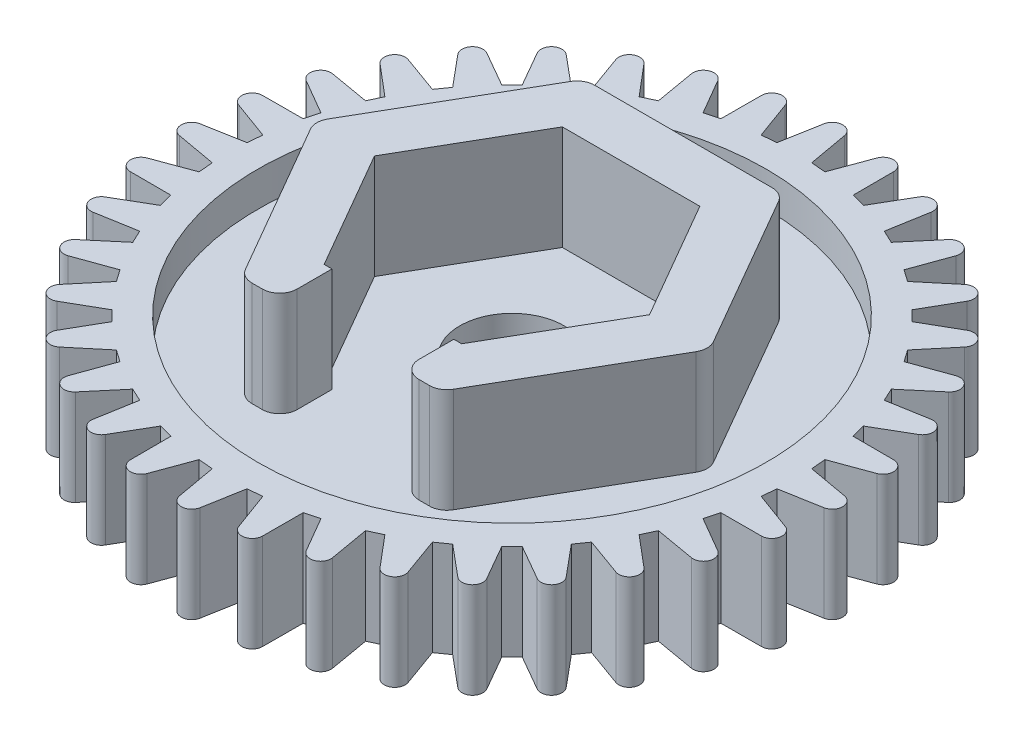
SolidWorks part; units mm, degrees
material "ABS"
ref_plane "Front Plane" through (0, 0, 0) normal (0, 0, 1) x (1, 0, 0)
ref_plane "Top Plane" through (0, 0, 0) normal (0, 1, 0) x (1, 0, 0)
ref_plane "Right Plane" through (0, 0, 0) normal (1, 0, 0) x (0, 0, -1)
sketch "Sketch1" plane through (0, 0, 0) normal (0, 0, 1) x (1, 0, 0)
  line L0 (1.5, 0) -> (7.3, 0)
  line L1 (7.3, 0) -> (7.3, 1)
  line L2 (7.3, 1) -> (9.5, 1)
  line L3 (9.5, 1) -> (9.5, -1.75)
  line L8 (0, 3) -> (0, 0) construction
  line L9 (7.3, -2) -> (1.5, -2)
  line L11 (7.3, -2) -> (7.3, -1.75)
  line L12 (7.3, -1.75) -> (9.5, -1.75)
  line L14 (1.5, -2) -> (1.5, 0)
  dimension "D1" = 19
  dimension "D2" = 2.2
  dimension "D4" = 0.25
  dimension "D5" = 2.75
  dimension "D8" = 3
revolve "Revolve1" add sketch "Sketch1" angle 360 about L8
sketch "Sketch2" plane through (0, 1, 0) normal (0, 1, 0) x (1, 0, 0)
  line L0 (0, 0) -> (0, 8.125) construction
  line L1 (0, 8.125) -> (0, 9.2) construction
  line L2 (-0.2953, 9.2529) -> (-0.5, 8.1096)
  line L3 (0, 9.2) -> (0, 9.5) construction
  line L4 (0.2953, 9.2529) -> (0.5, 8.1096)
  line L5 (1.8976, 9.061) -> (1.9006, 7.8996)
  line L6 (1.3159, 9.1636) -> (0.9158, 8.0732)
  line L7 (3.4422, 8.5939) -> (3.2435, 7.4495)
  line L8 (2.8872, 8.7959) -> (2.3038, 7.7915)
  line L9 (4.8822, 7.8656) -> (4.4878, 6.7731)
  line L10 (4.3707, 8.1609) -> (3.6218, 7.2731)
  line L11 (6.1738, 6.8983) -> (5.5958, 5.8909)
  line L12 (5.7214, 7.2779) -> (4.8297, 6.5337)
  line L13 (7.2779, 5.7214) -> (6.5337, 4.8297)
  line L14 (6.8983, 6.1738) -> (5.8909, 5.5958)
  line L15 (8.1609, 4.3707) -> (7.2731, 3.6218)
  line L16 (7.8656, 4.8822) -> (6.7731, 4.4878)
  line L17 (8.7959, 2.8872) -> (7.7915, 2.3038)
  line L18 (8.5939, 3.4422) -> (7.4495, 3.2435)
  line L19 (9.1636, 1.3159) -> (8.0732, 0.9158)
  line L20 (9.061, 1.8976) -> (7.8996, 1.9006)
  line L21 (9.2529, -0.2953) -> (8.1096, -0.5)
  line L22 (9.2529, 0.2953) -> (8.1096, 0.5)
  line L23 (9.061, -1.8976) -> (7.8996, -1.9006)
  line L24 (9.1636, -1.3159) -> (8.0732, -0.9158)
  line L25 (8.5939, -3.4422) -> (7.4495, -3.2435)
  line L26 (8.7959, -2.8872) -> (7.7915, -2.3038)
  line L27 (7.8656, -4.8822) -> (6.7731, -4.4878)
  line L28 (8.1609, -4.3707) -> (7.2731, -3.6218)
  line L29 (6.8983, -6.1738) -> (5.8909, -5.5958)
  line L30 (7.2779, -5.7214) -> (6.5337, -4.8297)
  line L31 (5.7214, -7.2779) -> (4.8297, -6.5337)
  line L32 (6.1738, -6.8983) -> (5.5958, -5.8909)
  line L33 (4.3707, -8.1609) -> (3.6218, -7.2731)
  line L34 (4.8822, -7.8656) -> (4.4878, -6.7731)
  line L35 (2.8872, -8.7959) -> (2.3038, -7.7915)
  line L36 (3.4422, -8.5939) -> (3.2435, -7.4495)
  line L37 (1.3159, -9.1636) -> (0.9158, -8.0732)
  line L38 (1.8976, -9.061) -> (1.9006, -7.8996)
  line L39 (-0.2953, -9.2529) -> (-0.5, -8.1096)
  line L40 (0.2953, -9.2529) -> (0.5, -8.1096)
  line L41 (-1.8976, -9.061) -> (-1.9006, -7.8996)
  line L42 (-1.3159, -9.1636) -> (-0.9158, -8.0732)
  line L43 (-3.4422, -8.5939) -> (-3.2435, -7.4495)
  line L44 (-2.8872, -8.7959) -> (-2.3038, -7.7915)
  line L45 (-4.8822, -7.8656) -> (-4.4878, -6.7731)
  line L46 (-4.3707, -8.1609) -> (-3.6218, -7.2731)
  line L47 (-6.1738, -6.8983) -> (-5.5958, -5.8909)
  line L48 (-5.7214, -7.2779) -> (-4.8297, -6.5337)
  line L49 (-7.2779, -5.7214) -> (-6.5337, -4.8297)
  line L50 (-6.8983, -6.1738) -> (-5.8909, -5.5958)
  line L51 (-8.1609, -4.3707) -> (-7.2731, -3.6218)
  line L52 (-7.8656, -4.8822) -> (-6.7731, -4.4878)
  line L53 (-8.7959, -2.8872) -> (-7.7915, -2.3038)
  line L54 (-8.5939, -3.4422) -> (-7.4495, -3.2435)
  line L55 (-9.1636, -1.3159) -> (-8.0732, -0.9158)
  line L56 (-9.061, -1.8976) -> (-7.8996, -1.9006)
  line L57 (-9.2529, 0.2953) -> (-8.1096, 0.5)
  line L58 (-9.2529, -0.2953) -> (-8.1096, -0.5)
  line L59 (-9.061, 1.8976) -> (-7.8996, 1.9006)
  line L60 (-9.1636, 1.3159) -> (-8.0732, 0.9158)
  line L61 (-8.5939, 3.4422) -> (-7.4495, 3.2435)
  line L62 (-8.7959, 2.8872) -> (-7.7915, 2.3038)
  line L63 (-7.8656, 4.8822) -> (-6.7731, 4.4878)
  line L64 (-8.1609, 4.3707) -> (-7.2731, 3.6218)
  line L65 (-6.8983, 6.1738) -> (-5.8909, 5.5958)
  line L66 (-7.2779, 5.7214) -> (-6.5337, 4.8297)
  line L67 (-5.7214, 7.2779) -> (-4.8297, 6.5337)
  line L68 (-6.1738, 6.8983) -> (-5.5958, 5.8909)
  line L69 (-4.3707, 8.1609) -> (-3.6218, 7.2731)
  line L70 (-4.8822, 7.8656) -> (-4.4878, 6.7731)
  line L71 (-2.8872, 8.7959) -> (-2.3038, 7.7915)
  line L72 (-3.4422, 8.5939) -> (-3.2435, 7.4495)
  line L73 (-1.3159, 9.1636) -> (-0.9158, 8.0732)
  line L74 (-1.8976, 9.061) -> (-1.9006, 7.8996)
  line L75 (0.5, 8.1096) -> (0.9158, 8.0732)
  line L76 (1.9006, 7.8996) -> (2.3038, 7.7915)
  line L77 (3.2435, 7.4495) -> (3.6218, 7.2731)
  line L78 (4.4878, 6.7731) -> (4.8297, 6.5337)
  line L79 (5.5958, 5.8909) -> (5.8909, 5.5958)
  line L80 (6.5337, 4.8297) -> (6.7731, 4.4878)
  line L81 (7.2731, 3.6218) -> (7.4495, 3.2435)
  line L82 (7.7915, 2.3038) -> (7.8996, 1.9006)
  line L83 (8.0732, 0.9158) -> (8.1096, 0.5)
  line L84 (8.1096, -0.5) -> (8.0732, -0.9158)
  line L85 (7.8996, -1.9006) -> (7.7915, -2.3038)
  line L86 (7.4495, -3.2435) -> (7.2731, -3.6218)
  line L87 (6.7731, -4.4878) -> (6.5337, -4.8297)
  line L88 (5.8909, -5.5958) -> (5.5958, -5.8909)
  line L89 (4.8297, -6.5337) -> (4.4878, -6.7731)
  line L90 (3.6218, -7.2731) -> (3.2435, -7.4495)
  line L91 (2.3038, -7.7915) -> (1.9006, -7.8996)
  line L92 (0.9158, -8.0732) -> (0.5, -8.1096)
  line L93 (-0.5, -8.1096) -> (-0.9158, -8.0732)
  line L94 (-1.9006, -7.8996) -> (-2.3038, -7.7915)
  line L95 (-3.2435, -7.4495) -> (-3.6218, -7.2731)
  line L96 (-4.4878, -6.7731) -> (-4.8297, -6.5337)
  line L97 (-5.5958, -5.8909) -> (-5.8909, -5.5958)
  line L98 (-6.5337, -4.8297) -> (-6.7731, -4.4878)
  line L99 (-7.2731, -3.6218) -> (-7.4495, -3.2435)
  line L100 (-7.7915, -2.3038) -> (-7.8996, -1.9006)
  line L101 (-8.0732, -0.9158) -> (-8.1096, -0.5)
  line L102 (-8.1096, 0.5) -> (-8.0732, 0.9158)
  line L103 (-7.8996, 1.9006) -> (-7.7915, 2.3038)
  line L104 (-7.4495, 3.2435) -> (-7.2731, 3.6218)
  line L105 (-6.7731, 4.4878) -> (-6.5337, 4.8297)
  line L106 (-5.8909, 5.5958) -> (-5.5958, 5.8909)
  line L107 (-4.8297, 6.5337) -> (-4.4878, 6.7731)
  line L108 (-3.6218, 7.2731) -> (-3.2435, 7.4495)
  line L109 (-2.3038, 7.7915) -> (-1.9006, 7.8996)
  line L110 (-0.9158, 8.0732) -> (-0.5, 8.1096)
  line L111 (0, 0) -> (-9.5, 9.5) construction
  circle A0 centre (0, 0) radius 8.125 construction
  arc A1 (0.2953, 9.2529) -> (-0.2953, 9.2529) centre (0, 9.2) ccw
  circle A2 centre (0, 0) radius 9.5 construction
  arc A3 (1.8976, 9.061) -> (1.3159, 9.1636) centre (1.5976, 9.0602) ccw
  arc A4 (3.4422, 8.5939) -> (2.8872, 8.7959) centre (3.1466, 8.6452) ccw
  arc A5 (4.8822, 7.8656) -> (4.3707, 8.1609) centre (4.6, 7.9674) ccw
  arc A6 (6.1738, 6.8983) -> (5.7214, 7.2779) centre (5.9136, 7.0476) ccw
  arc A7 (7.2779, 5.7214) -> (6.8983, 6.1738) centre (7.0476, 5.9136) ccw
  arc A8 (8.1609, 4.3707) -> (7.8656, 4.8822) centre (7.9674, 4.6) ccw
  arc A9 (8.7959, 2.8872) -> (8.5939, 3.4422) centre (8.6452, 3.1466) ccw
  arc A10 (9.1636, 1.3159) -> (9.061, 1.8976) centre (9.0602, 1.5976) ccw
  arc A11 (9.2529, -0.2953) -> (9.2529, 0.2953) centre (9.2, 0) ccw
  arc A12 (9.061, -1.8976) -> (9.1636, -1.3159) centre (9.0602, -1.5976) ccw
  arc A13 (8.5939, -3.4422) -> (8.7959, -2.8872) centre (8.6452, -3.1466) ccw
  arc A14 (7.8656, -4.8822) -> (8.1609, -4.3707) centre (7.9674, -4.6) ccw
  arc A15 (6.8983, -6.1738) -> (7.2779, -5.7214) centre (7.0476, -5.9136) ccw
  arc A16 (5.7214, -7.2779) -> (6.1738, -6.8983) centre (5.9136, -7.0476) ccw
  arc A17 (4.3707, -8.1609) -> (4.8822, -7.8656) centre (4.6, -7.9674) ccw
  arc A18 (2.8872, -8.7959) -> (3.4422, -8.5939) centre (3.1466, -8.6452) ccw
  arc A19 (1.3159, -9.1636) -> (1.8976, -9.061) centre (1.5976, -9.0602) ccw
  arc A20 (-0.2953, -9.2529) -> (0.2953, -9.2529) centre (0, -9.2) ccw
  arc A21 (-1.8976, -9.061) -> (-1.3159, -9.1636) centre (-1.5976, -9.0602) ccw
  arc A22 (-3.4422, -8.5939) -> (-2.8872, -8.7959) centre (-3.1466, -8.6452) ccw
  arc A23 (-4.8822, -7.8656) -> (-4.3707, -8.1609) centre (-4.6, -7.9674) ccw
  arc A24 (-6.1738, -6.8983) -> (-5.7214, -7.2779) centre (-5.9136, -7.0476) ccw
  arc A25 (-7.2779, -5.7214) -> (-6.8983, -6.1738) centre (-7.0476, -5.9136) ccw
  arc A26 (-8.1609, -4.3707) -> (-7.8656, -4.8822) centre (-7.9674, -4.6) ccw
  arc A27 (-8.7959, -2.8872) -> (-8.5939, -3.4422) centre (-8.6452, -3.1466) ccw
  arc A28 (-9.1636, -1.3159) -> (-9.061, -1.8976) centre (-9.0602, -1.5976) ccw
  arc A29 (-9.2529, 0.2953) -> (-9.2529, -0.2953) centre (-9.2, 0) ccw
  arc A30 (-9.061, 1.8976) -> (-9.1636, 1.3159) centre (-9.0602, 1.5976) ccw
  arc A31 (-8.5939, 3.4422) -> (-8.7959, 2.8872) centre (-8.6452, 3.1466) ccw
  arc A32 (-7.8656, 4.8822) -> (-8.1609, 4.3707) centre (-7.9674, 4.6) ccw
  arc A33 (-6.8983, 6.1738) -> (-7.2779, 5.7214) centre (-7.0476, 5.9136) ccw
  arc A34 (-5.7214, 7.2779) -> (-6.1738, 6.8983) centre (-5.9136, 7.0476) ccw
  arc A35 (-4.3707, 8.1609) -> (-4.8822, 7.8656) centre (-4.6, 7.9674) ccw
  arc A36 (-2.8872, 8.7959) -> (-3.4422, 8.5939) centre (-3.1466, 8.6452) ccw
  arc A37 (-1.3159, 9.1636) -> (-1.8976, 9.061) centre (-1.5976, 9.0602) ccw
  circle A38 centre (0, 0) radius 13.435
  point P14 (-9.5, 9.5)
  point P191 (0, 0)
  point P262 (0, 0)
  dimension "D1" = 16.25
  dimension "D2" = 0.3
  dimension "D3" = 1
  dimension "D4" = 36
  dimension "D6" = 45
  dimension "D5" = 36
extrude "Cut-Extrude1" cut sketch "Sketch2" against normal up to surface (2.75 mm away) up to face at (0, -1.75, 9.5)
sketch "Sketch3" plane through (0, 0, 0) normal (0, 1, 0) x (1, 0, 0)
  line L0 (0, 0) -> (-3.95, 0) construction
  line L1 (-3.95, 0) -> (-1.975, -3.4208)
  line L2 (-1.975, -3.4208) -> (-1.75, -3.4208)
  line L3 (1.975, -3.4208) -> (3.95, 0)
  line L4 (3.95, 0) -> (1.975, 3.4208)
  line L5 (1.975, 3.4208) -> (-1.975, 3.4208)
  line L6 (-1.975, 3.4208) -> (-3.95, 0)
  line L7 (-5.5377, -0.25) -> (-2.9854, -4.6708)
  line L8 (-2.5524, -4.9208) -> (-2.25, -4.9208)
  line L9 (2.9854, -4.6708) -> (5.5377, -0.25)
  line L10 (5.5377, 0.25) -> (2.9854, 4.6708)
  line L11 (2.5524, 4.9208) -> (-2.5524, 4.9208)
  line L12 (-2.9854, 4.6708) -> (-5.5377, 0.25)
  line L13 (0, 0) -> (-5.6821, 0) construction
  line L14 (0, 0) -> (0, -4.9208) construction
  line L15 (-1.75, -3.4208) -> (-1.75, -4.4208)
  line L16 (1.75, -3.4208) -> (1.75, -4.4208)
  line L17 (1.75, -3.4208) -> (1.975, -3.4208)
  line L18 (2.25, -4.9208) -> (2.5524, -4.9208)
  circle A0 centre (0, 0) radius 3.4208 construction
  circle A1 centre (0, 0) radius 4.9208 construction
  arc A2 (1.75, -4.4208) -> (2.25, -4.9208) centre (2.25, -4.4208) ccw
  arc A3 (-1.75, -4.4208) -> (-2.25, -4.9208) centre (-2.25, -4.4208) cw
  arc A4 (2.5524, -4.9208) -> (2.9854, -4.6708) centre (2.5524, -4.4208) ccw
  arc A5 (5.5377, -0.25) -> (5.5377, 0.25) centre (5.1047, 0) ccw
  arc A6 (2.9854, 4.6708) -> (2.5524, 4.9208) centre (2.5524, 4.4208) ccw
  arc A7 (-2.5524, 4.9208) -> (-2.9854, 4.6708) centre (-2.5524, 4.4208) ccw
  arc A8 (-5.5377, -0.25) -> (-5.5377, 0.25) centre (-5.1047, 0) cw
  arc A9 (-2.9854, -4.6708) -> (-2.5524, -4.9208) centre (-2.5524, -4.4208) ccw
  point P23 (1.75, -4.9208)
  point P26 (-1.75, -4.9208)
  dimension "D4" = 0.5
  dimension "D1" = 7.9
  dimension "D2" = 1.5
  dimension "D3" = 3.5
extrude "Boss-Extrude1" add sketch "Sketch3" along normal blind 3
